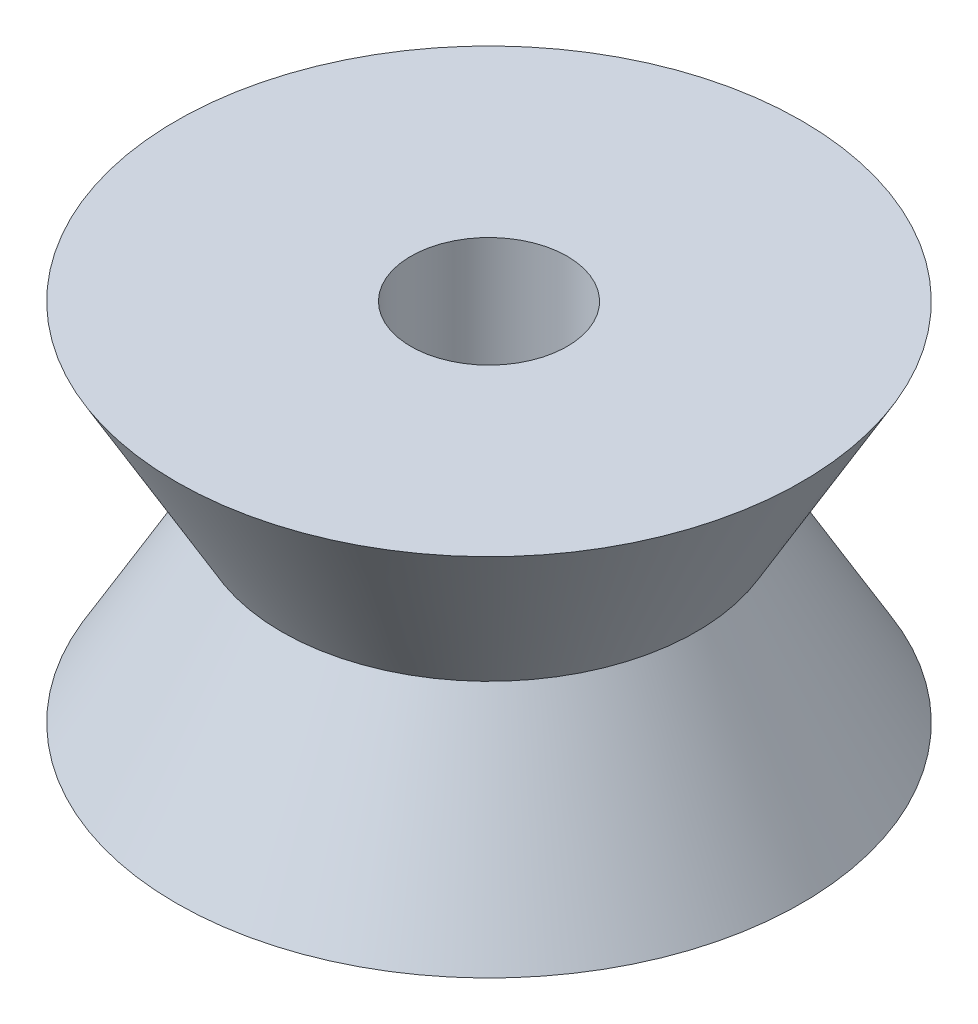
SolidWorks part; units mm, degrees
ref_plane "Plan de face" through (0, 0, 0) normal (0, 0, 1) x (1, 0, 0)
ref_plane "Plan de dessus" through (0, 0, 0) normal (0, 1, 0) x (1, 0, 0)
ref_plane "Plan de droite" through (0, 0, 0) normal (1, 0, 0) x (0, 0, -1)
sketch "Esquisse2" plane through (0, 0, 0) normal (0, 0, 1) x (1, 0, 0)
  line L0 (0, 0) -> (0, 23.4649) construction
  line L1 (1.5, -3.5) -> (1.5, 3.5)
  line L2 (1.5, 3.5) -> (6, 3.5)
  line L3 (6, 3.5) -> (3.9793, 0)
  line L4 (0, 0) -> (32.554, 0) construction
  line L5 (6, -3.5) -> (3.9793, 0)
  line L6 (1.5, -3.5) -> (6, -3.5)
  point P10 (1.5, 0)
  dimension "D1" = 120
  dimension "D2" = 3
  dimension "D3" = 7
  dimension "12" = 12
revolve "Révolution1" add sketch "Esquisse2" angle 360 about L0
